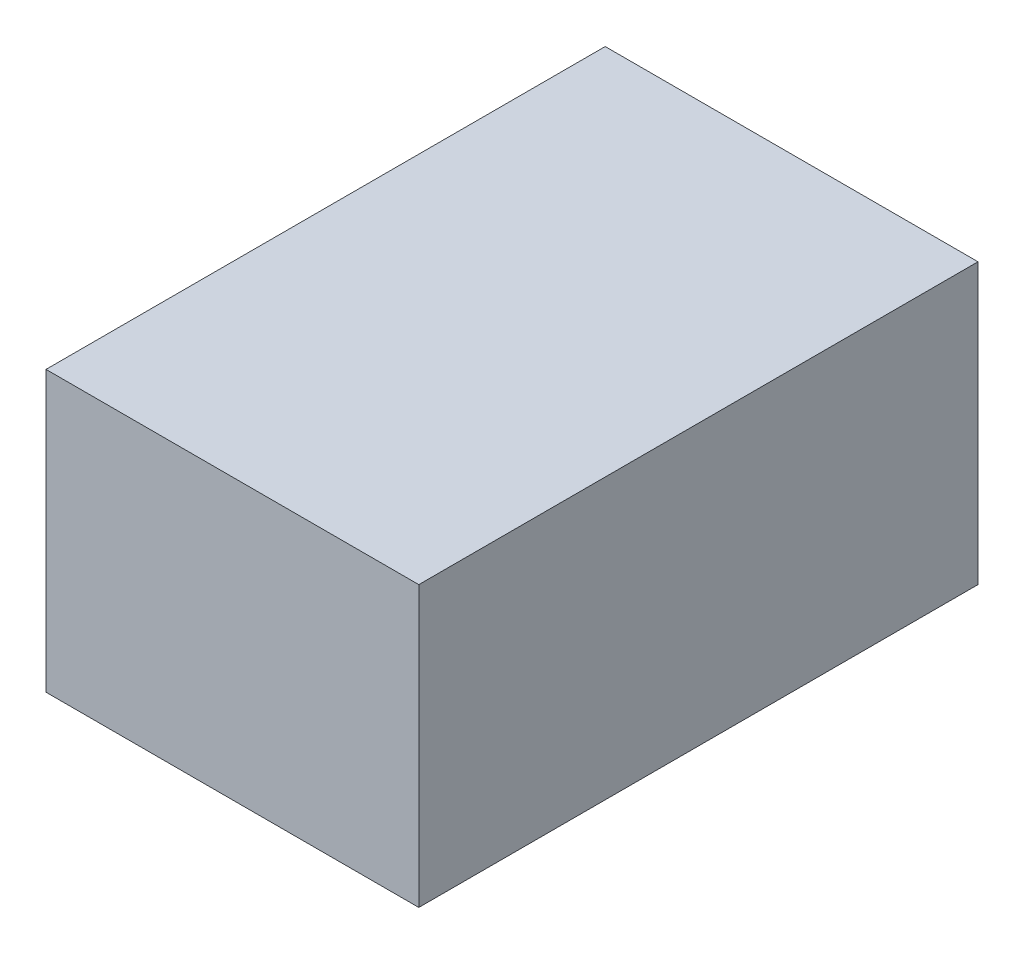
SolidWorks part; units mm, degrees
ref_plane "Front Plane" through (0, 0, 0) normal (0, 0, 1) x (1, 0, 0)
ref_plane "Top Plane" through (0, 0, 0) normal (0, 1, 0) x (1, 0, 0)
ref_plane "Right Plane" through (0, 0, 0) normal (1, 0, 0) x (0, 0, -1)
sketch "Sketch1" plane through (0, 0, 0) normal (0, 1, 0) x (1, 0, 0)
  line L1 (50.8, 76.2) -> (-50.8, 76.2)
  line L2 (50.8, 76.2) -> (50.8, -76.2)
  line L3 (50.8, -76.2) -> (-50.8, -76.2)
  line L4 (-50.8, 76.2) -> (-50.8, -76.2)
  line L5 (50.8, 76.2) -> (-50.8, -76.2) construction
  line L6 (50.8, -76.2) -> (-50.8, 76.2) construction
  point P0 (0, 0)
  point P6 (0, -76.2)
  dimension "D1" = 152.4
  dimension "D2" = 101.6
extrude "Boss-Extrude1" add sketch "Sketch1" along normal blind 76.2
